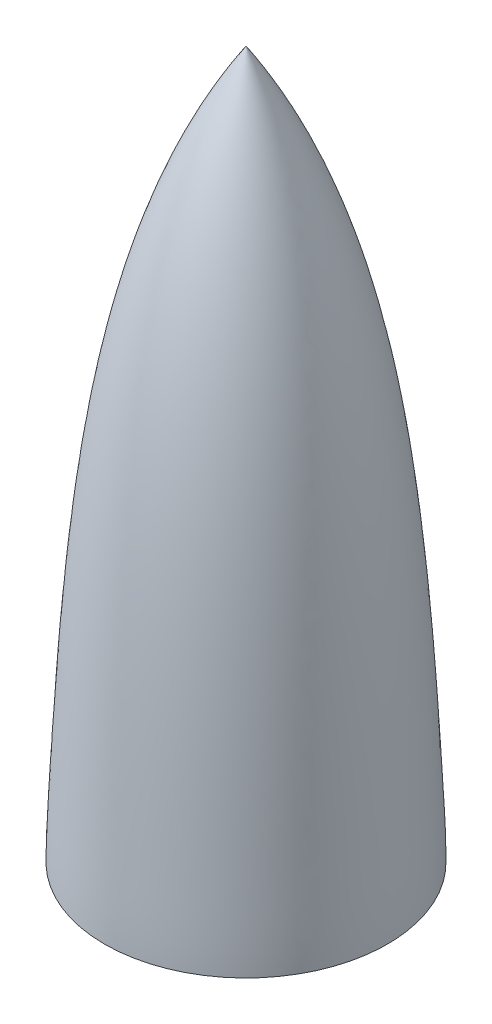
SolidWorks part; units mm, degrees
ref_plane "Front Plane" through (0, 0, 0) normal (0, 0, 1) x (1, 0, 0)
ref_plane "Top Plane" through (0, 0, 0) normal (0, 1, 0) x (1, 0, 0)
ref_plane "Right Plane" through (0, 0, 0) normal (1, 0, 0) x (0, 0, -1)
sketch "Sketch1" plane through (0, 0, 0) normal (1, 0, 0) x (0, 0, -1)
  line L0 (78.359, 0) -> (0, 0)
  line L1 (0, 0) -> (0, 391.795) construction
  line L2 (78.359, 0) -> (78.359, -50.8) construction
  line L3 (76.2, 0) -> (76.2, -50.8) construction
  line L4 (0, 391.795) -> (0, 387.7903)
  spline S0 degree 3 poles (0, 391.795) (43.3405, 325.2215) (68.729, 202.6674) (75.6423, 68.4476) (78.359, 11.9132) (78.359, 0) knots 0 0 0 0 0.579779 0.911589 1 1 1 1
  spline S1 degree 3 poles (0, 387.7903) (29.8234, 338.9407) (60.242, 238.0075) (70.9113, 117.0624) (74.7976, 41.4641) (76.2, 11.681) (76.2, 0) knots 0 0 0 0 0.428746 0.778809 0.910512 1 1 1 1
  point P0 (78.359, 0)
  point P3 (0, 391.795)
  point P6 (76.2, 0)
  point P9 (0, 391.795)
  point P12 (0, 387.7903)
  dimension "D1" = 78.359
  dimension "D2" = 391.795
  dimension "D4" = 50.8
  dimension "D5" = 2.159
revolve "Revolve1" add sketch "Sketch1" angle 360 about L1
